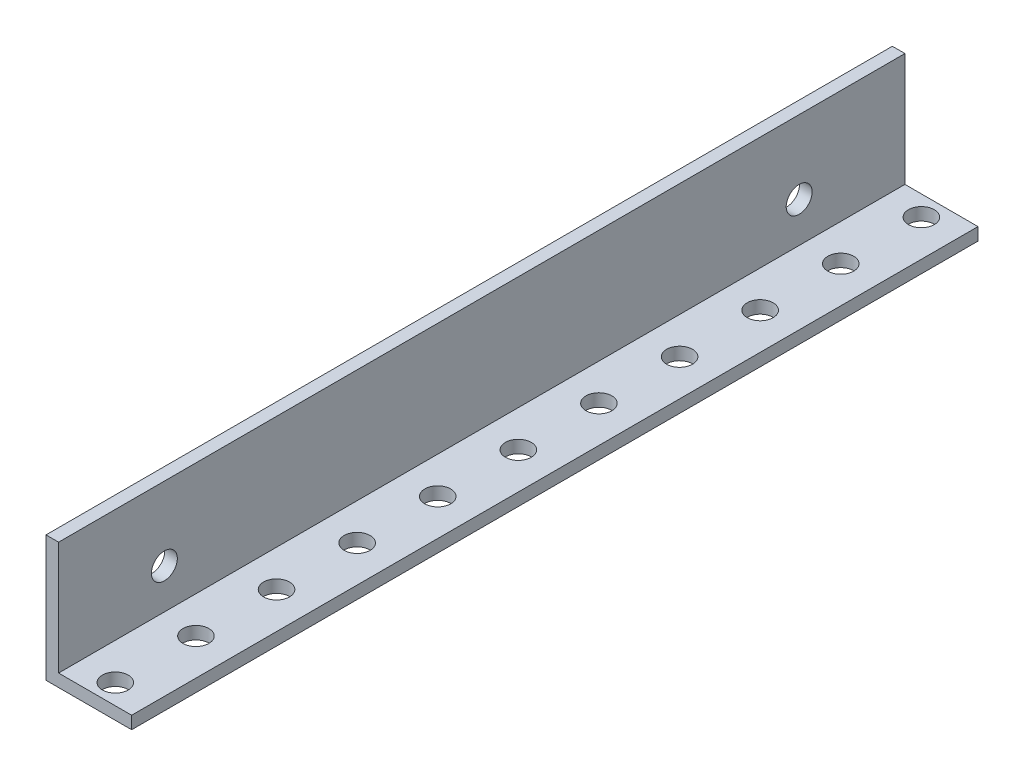
SolidWorks part; units mm, degrees
material "6061-T6 (SS)"
ref_plane "Front Plane" through (0, 0, 0) normal (0, 0, 1) x (1, 0, 0)
ref_plane "Top Plane" through (0, 0, 0) normal (0, 1, 0) x (1, 0, 0)
ref_plane "Right Plane" through (0, 0, 0) normal (1, 0, 0) x (0, 0, -1)
sketch "Sketch1" plane through (0, 0, 0) normal (0, 0, 1) x (1, 0, 0)
  line L0 (0, 0) -> (0, 15.875)
  line L1 (0, 15.875) -> (1.5875, 15.875)
  line L2 (1.5875, 15.875) -> (1.5875, 1.5875)
  line L3 (1.5875, 1.5875) -> (10.795, 1.5875)
  line L4 (10.795, 1.5875) -> (10.795, 0)
  line L5 (10.795, 0) -> (0, 0)
  dimension "D1" = 15.875
  dimension "D2" = 1.5875
  dimension "D3" = 10.795
extrude "Extrude1" add sketch "Sketch1" along normal mid plane 106.68
sketch "Sketch2" plane through (0, 1.5875, 0) normal (0, 1, 0) x (1, 0, 0)
  line L0 (10.795, 0) -> (6.1976, 0) construction
  line L1 (6.1976, 0) -> (1.5875, 0) construction
  line L2 (10.795, -53.34) -> (10.795, 53.34) construction
  line L3 (1.5875, -53.34) -> (1.5875, 53.34) construction
  dimension "D1" = 4.6101
hole_wizard "#4 Clearance Hole1" positions "3DSketch1" profile "Sketch3" hole size "#4" standard "Ansi Inch"
sketch3d "3DSketch1"
  point P4 (6.1976, 1.5875, 0)
sketch "Sketch3" plane through (6.1976, 1.5875, 0) normal (1, 0, 0) x (0, 0, 1)
  line L0 (0, 0) -> (0, 16.2206)
  line L1 (0, 16.2206) -> (1.6319, 15.24)
  line L2 (1.6319, 15.24) -> (1.6319, 0)
  line L5 (1.6319, 0) -> (0, 0)
  line L10 (0, 16.2206) -> (-1.6319, 15.24) construction
  line L11 (0, -6.35) -> (0, 107.95) construction
  dimension "Hole Dia." = 3.2639
  dimension "Hole Depth" = 15.24
  dimension "Drill Angle" = 118
pattern_linear "LPattern1" count 6 spacing 10.16 along (0, 0, 1) count 6 spacing 10.16 along (0, 0, -1) of "#4 Clearance Hole1"
sketch "Sketch4" plane through (1.5875, 0, 0) normal (1, 0, 0) x (0, 0, -1)
  line L0 (40.005, 1.5875) -> (40.005, 6.6218) construction
  line L1 (-40.005, 1.5875) -> (-40.005, 6.6218) construction
  line L2 (-53.34, 1.5875) -> (53.34, 1.5875) construction
  line L4 (40.005, 6.6218) -> (0, 6.6218) construction
  line L5 (0, 6.6218) -> (-40.005, 6.6218) construction
  line L6 (0, 1.5875) -> (0, 6.6218) construction
  point P6 (-63.5, 7.1437)
  dimension "D1" = 40.005
  dimension "D2" = 5.0343
hole_wizard "#4 Clearance Hole2" positions "3DSketch2" profile "Sketch5" hole size "#4" standard "Ansi Inch"
sketch3d "3DSketch2"
  point P9 (1.5875, 6.6218, -40.005)
  point P13 (1.5875, 6.6218, 40.005)
sketch "Sketch5" plane through (1.5875, 6.6218, -40.005) normal (0, 1, 0) x (0, 0, -1)
  line L0 (0, 0) -> (0, 16.2206)
  line L1 (0, 16.2206) -> (1.6319, 15.24)
  line L2 (1.6319, 15.24) -> (1.6319, 0)
  line L5 (1.6319, 0) -> (0, 0)
  line L10 (0, 16.2206) -> (-1.6319, 15.24) construction
  line L11 (0, -6.35) -> (0, 107.95) construction
  dimension "Hole Dia." = 3.2639
  dimension "Hole Depth" = 15.24
  dimension "Drill Angle" = 118
chamfer "Chamfer1" [suppressed] distance 10.16 angle 45
